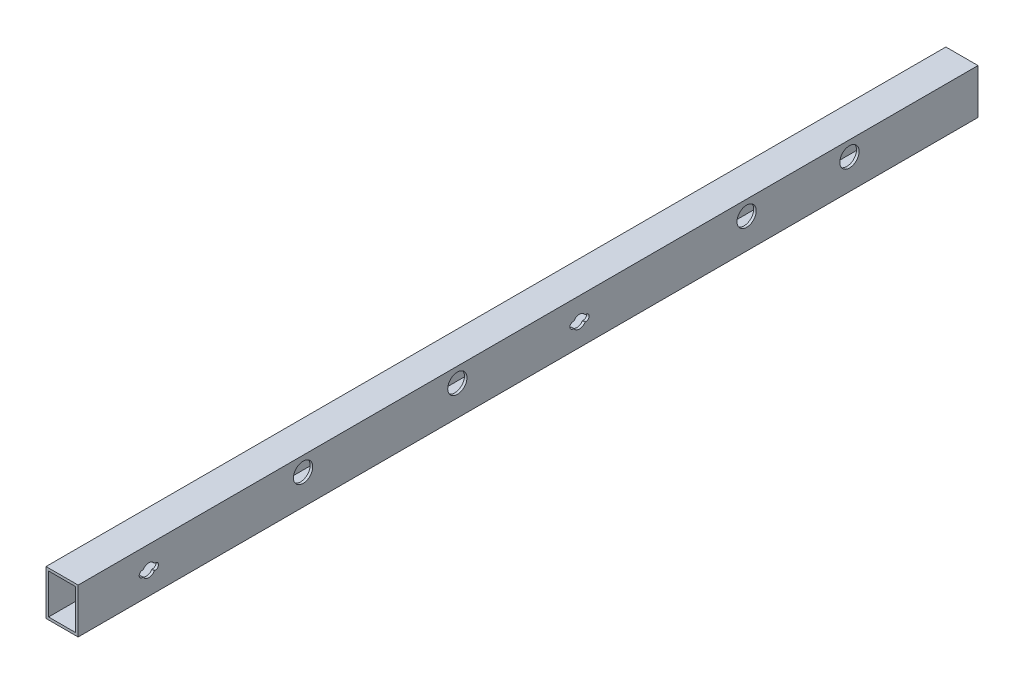
SolidWorks part; units mm, degrees
ref_plane "Front Plane" through (0, 0, 0) normal (0, 0, 1) x (1, 0, 0)
ref_plane "Top Plane" through (0, 0, 0) normal (0, 1, 0) x (1, 0, 0)
ref_plane "Right Plane" through (0, 0, 0) normal (1, 0, 0) x (0, 0, -1)
sketch "Sketch1" plane through (0, 0, 0) normal (0, 0, 1) x (1, 0, 0)
  line L1 (0, 0) -> (50, 0)
  line L2 (0, 0) -> (0, -70)
  line L3 (0, -70) -> (50, -70)
  line L4 (50, 0) -> (50, -70)
  line L5 (4, -4) -> (46, -4)
  line L6 (4, -4) -> (4, -66)
  line L7 (4, -66) -> (46, -66)
  line L8 (46, -4) -> (46, -66)
  dimension "D1" = 70
  dimension "D2" = 50
  dimension "D3" = 4
  dimension "D4" = 4
  dimension "D5" = 4
  dimension "D6" = 4
extrude "Boss-Extrude2" add sketch "Sketch1" along normal blind 1400
sketch "Sketch2" plane through (50, 0, 0) normal (1, 0, 0) x (0, 0, -1)
  line L0 (-1400, -70) -> (-1400, 0) construction
  line L1 (-1400, 0) -> (0, 0) construction
  line L2 (-1281.3397, -30) -> (-1280, -30)
  line L3 (-1300, -35) -> (-1280, -35) construction
  line L4 (-1300, -30) -> (-1298.6603, -30)
  line L5 (-1300, -40) -> (-1298.6603, -40)
  line L6 (-1400, -70) -> (0, -70) construction
  line L7 (-1281.3397, -40) -> (-1280, -40)
  line L8 (-611.3397, -30) -> (-610, -30)
  line L9 (-630, -35) -> (-610, -35) construction
  line L10 (-630, -30) -> (-628.6603, -30)
  line L11 (-630, -40) -> (-628.6603, -40)
  line L12 (-611.3397, -40) -> (-610, -40)
  circle A0 centre (-1050, -23) radius 15
  circle A1 centre (-200, -23) radius 15
  circle A2 centre (-810, -23) radius 15
  circle A3 centre (-360, -23) radius 15
  arc A6 (-1300, -30) -> (-1300, -40) centre (-1300, -35) ccw
  arc A7 (-1280, -40) -> (-1280, -30) centre (-1280, -35) ccw
  arc A8 (-1281.3397, -30) -> (-1298.6603, -30) centre (-1290, -35) ccw
  arc A9 (-1298.6603, -40) -> (-1281.3397, -40) centre (-1290, -35) ccw
  arc A10 (-630, -30) -> (-630, -40) centre (-630, -35) ccw
  arc A11 (-610, -40) -> (-610, -30) centre (-610, -35) ccw
  arc A12 (-611.3397, -30) -> (-628.6603, -30) centre (-620, -35) ccw
  arc A13 (-628.6603, -40) -> (-611.3397, -40) centre (-620, -35) ccw
  point P16 (-1290, -35)
  point P29 (-620, -35)
  dimension "D1" = 30
  dimension "D2" = 30
  dimension "D3" = 30
  dimension "D4" = 30
  dimension "D12" = 5
  dimension "D16" = 20
  dimension "D19" = 5
  dimension "D11" = 5
  dimension "D24" = 20
  dimension "D27" = 5
  dimension "D5" = 350
  dimension "D6" = 240
  dimension "D7" = 450
  dimension "D8" = 160
  dimension "D9" = 23
  dimension "D10" = 35
  dimension "D13" = 20
  dimension "D15" = 100
  dimension "D17" = 5
  dimension "D18" = 5
  dimension "D20" = 10
  dimension "D21" = 10
  dimension "D22" = 1.3397
  dimension "D23" = 1.3397
  dimension "D14" = 20
  dimension "D25" = 5
  dimension "D26" = 5
  dimension "D28" = 10
  dimension "D29" = 10
  dimension "D30" = 1.3397
  dimension "D31" = 1.3397
  dimension "D32" = 35
  dimension "D33" = 260
extrude "Cut-Extrude1" cut sketch "Sketch2" against normal through all
equation "\"D4@Sketch1\"=\"D3@Sketch1\""
equation "\"D5@Sketch1\"=\"D3@Sketch1\""
equation "\"D2@Sketch2\"=\"D1@Sketch2\""
